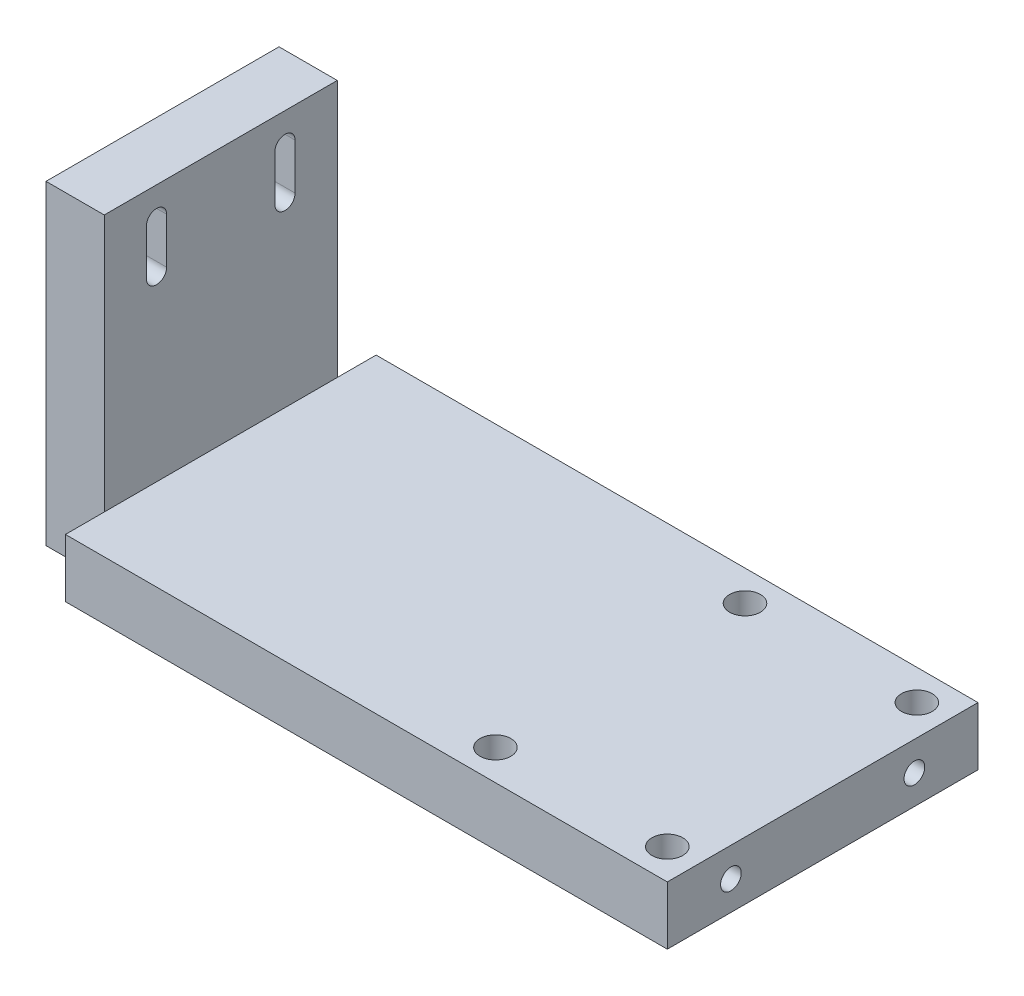
SolidWorks part; units mm, degrees
material "6061-O (SS)"
ref_plane "Alzado" through (0, 0, 0) normal (0, 0, 1) x (1, 0, 0)
ref_plane "Planta" through (0, 0, 0) normal (0, 1, 0) x (1, 0, 0)
ref_plane "Vista lateral" through (0, 0, 0) normal (1, 0, 0) x (0, 0, -1)
sketch "Croquis1" plane through (0, 0, 0) normal (0, 0, 1) x (1, 0, 0)
  line L0 (0, 93.65) -> (0, 0)
  line L1 (0, 0) -> (206.35, 0)
  dimension "D1" = 93.65
  dimension "D2" = 206.35
ref_plane "Plano1" through (0, 0, 0) normal (1, 0, 0) x (0, 1, 0)
other "Solid 3 X 0.75(1)"
ref_plane "Plano2" through (0, 0, 0) normal (1, 0, 0) x (0, 0, 1)
sketch "Croquis18" plane through (0, 0, 0) normal (1, 0, 0) x (0, 0, 1)
  line L1 (50.8, 9.525) -> (-50.8, 9.525)
  line L2 (50.8, 9.525) -> (50.8, -9.525)
  line L3 (50.8, -9.525) -> (-50.8, -9.525)
  line L4 (-50.8, 9.525) -> (-50.8, -9.525)
  line L5 (50.8, 9.525) -> (-50.8, -9.525) construction
  line L6 (50.8, -9.525) -> (-50.8, 9.525) construction
  point P0 (0, 0)
  point P5 (0, 0)
  dimension "D1" = 19.05
  dimension "D2" = 101.6
sketch "Croquis12" plane through (9.525, 0, 0) normal (1, 0, 0) x (0, 0, -1)
  line L0 (0, 0) -> (0, 50000) construction
  line L1 (-21, 83.65) -> (-21, 68.65) construction
  line L2 (-17.7, 83.65) -> (-17.7, 68.65)
  line L3 (-24.3, 83.65) -> (-24.3, 68.65)
  line L4 (21, 83.65) -> (21, 68.65) construction
  line L5 (17.7, 83.65) -> (17.7, 68.65)
  line L6 (24.3, 83.65) -> (24.3, 68.65)
  arc A0 (-17.7, 83.65) -> (-24.3, 83.65) centre (-21, 83.65) ccw
  arc A1 (-24.3, 68.65) -> (-17.7, 68.65) centre (-21, 68.65) ccw
  arc A2 (17.7, 83.65) -> (24.3, 83.65) centre (21, 83.65) cw
  arc A3 (24.3, 68.65) -> (17.7, 68.65) centre (21, 68.65) cw
  point P5 (-21, 76.15)
  point P13 (21, 76.15)
  dimension "D1" = 3.3
  dimension "D2" = 10
  dimension "D3" = 15
extrude "Cortar-Extruir1" cut sketch "Croquis12" against normal through all
hole_wizard "Taladro de margen para 3/81" positions "Croquis13" profile "Croquis14" hole size "3/8" standard "Ansi Inch" end condition through all
sketch "Croquis13" plane through (0, 9.525, 0) normal (0, 1, 0) x (1, 0, 0)
  line L1 (0, 0) -> (50000, 0) construction
  line L3 (206.35, 50.8) -> (206.35, -50.8) construction
  line L5 (206.35, -50.8) -> (9.525, -50.8) construction
  point P0 (196.35, -40.8)
  point P9 (140.15, -40.8)
  point P19 (196.35, 40.8)
  point P20 (140.15, 40.8)
  dimension "D2" = 10
  dimension "D3" = 56.2
  dimension "D1" = 10
sketch "Croquis14" plane through (196.35, 9.525, 40.8) normal (1, 0, 0) x (0, 0, 1)
  line L0 (0, 0) -> (0, 19.05)
  line L1 (0, 19.05) -> (5.0419, 19.05)
  line L2 (5.0419, 19.05) -> (5.0419, 0)
  line L5 (5.0419, 0) -> (0, 0)
  line L11 (0, -6.35) -> (0, 107.95) construction
  dimension "Diámetro de taladro hasta el siguiente" = 10.0838
  dimension "Profundidad de taladro hasta el siguiente" = 19.05
sketch "Sketch3" plane through (0, 93.65, 0) normal (0, 1, 0) x (1, 0, 0)
  line L1 (0, 0) -> (-50000, 0) construction
  line L2 (9.525, -50.8) -> (9.525, 50.8) construction
  line L3 (-9.525, -50.8) -> (9.525, -50.8)
  line L4 (-9.525, -50.8) -> (-9.525, -38.1)
  line L5 (-9.525, -38.1) -> (9.525, -38.1)
  line L6 (9.525, -50.8) -> (9.525, -38.1)
  line L7 (9.525, 50.8) -> (9.525, 38.1)
  line L8 (-9.525, 38.1) -> (9.525, 38.1)
  line L9 (-9.525, 50.8) -> (-9.525, 38.1)
  line L10 (-9.525, 50.8) -> (9.525, 50.8)
  dimension "D1" = 12.7
extrude "Cut-Extrude2" cut sketch "Sketch3" against normal through all
hole_wizard "CBORE for 1/4 Socket Head Cap Screw1" positions "Sketch4" profile "Sketch6" counterbore size "1/4" standard "ANSI Inch"
sketch "Sketch4" plane through (-9.525, 0, 0) normal (-1, 0, 0) x (0, 0, 1)
  line L0 (0, 0) -> (0, 50000) construction
  point P0 (30, 0)
  point P10 (-30, 0)
  dimension "D1" = 30
sketch "Sketch6" plane through (-9.525, 0, 30) normal (0, 1, 0) x (0, 0, 1)
  line L0 (0, 0) -> (0, 40.1298)
  line L1 (0, 40.1298) -> (3.3782, 38.1)
  line L2 (3.3782, 38.1) -> (3.3782, 6.35)
  line L3 (3.3782, 6.35) -> (5.5562, 6.35)
  line L4 (5.5562, 6.35) -> (5.5562, 0)
  line L5 (5.5562, 0) -> (0, 0)
  line L10 (0, 40.1298) -> (-3.3782, 38.1) construction
  line L11 (0, -6.35) -> (0, 107.95) construction
  dimension "Hole Dia." = 6.7564
  dimension "Hole Depth" = 38.1
  dimension "C'Bore Dia." = 11.1125
  dimension "C'Bore Depth" = 6.35
  dimension "Drill Angle" = 118
ref_plane "Plane1" through (107.9375, 0, 0) normal (-1, 0, 0) x (0, 0, 1)
mirror "Mirror1" about plane through (107.9375, 0, 0) normal (-1, 0, 0) of "CBORE for 1/4 Socket Head Cap Screw1"
equation "\"D2@Croquis13\"=\"D1@Croquis13\""
